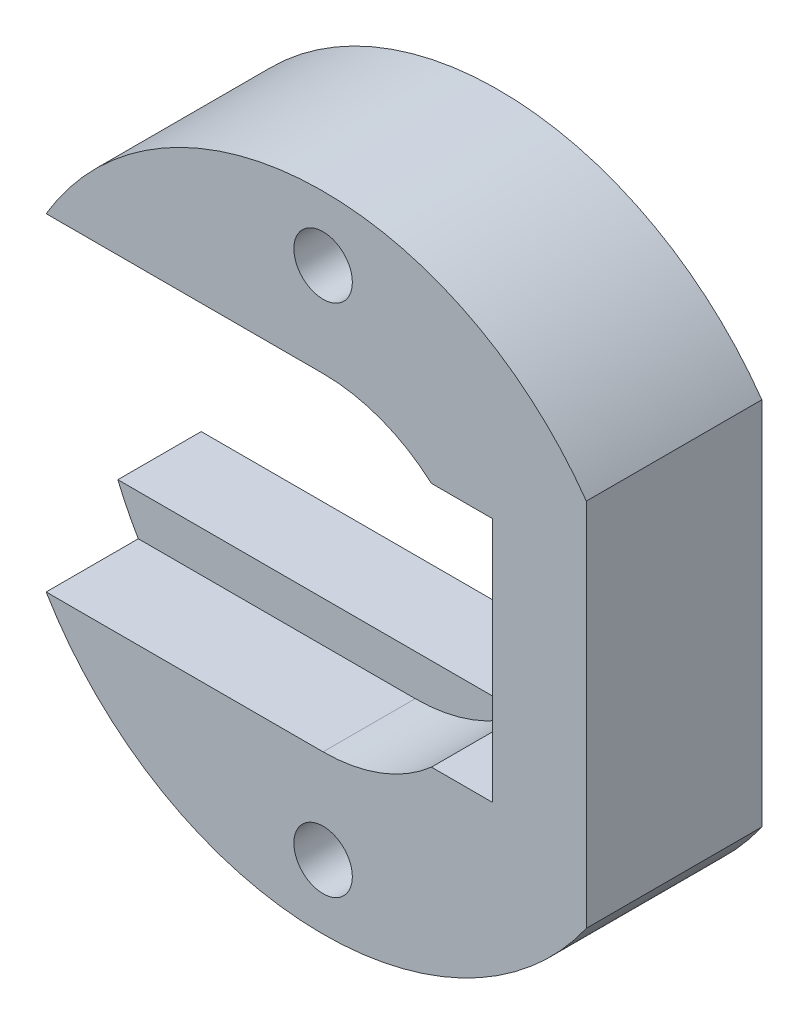
SolidWorks part; units mm, degrees
ref_plane "Front Plane" through (0, 0, 0) normal (0, 0, 1) x (1, 0, 0)
ref_plane "Top Plane" through (0, 0, 0) normal (0, 1, 0) x (1, 0, 0)
ref_plane "Right Plane" through (0, 0, 0) normal (1, 0, 0) x (0, 0, -1)
sketch "Sketch1" plane through (0, 0, 0) normal (0, 0, 1) x (1, 0, 0)
  circle A0 centre (0, 0) radius 34.925
  dimension "D1" = 69.85
extrude "Boss-Extrude1" add sketch "Sketch1" along normal blind 19.05
sketch "Sketch2" plane through (0, 0, 19.05) normal (0, 0, 1) x (1, 0, 0)
  line L1 (18.415, -13.335) -> (-88.265, -13.335)
  line L2 (18.415, -13.335) -> (18.415, 13.335)
  line L3 (18.415, 13.335) -> (-88.265, 13.335)
  line L4 (-88.265, -13.335) -> (-88.265, 13.335)
  line L5 (18.415, -13.335) -> (-88.265, 13.335) construction
  line L6 (18.415, 13.335) -> (-88.265, -13.335) construction
  circle A0 centre (0, 0) radius 34.925 construction
  point P0 (-34.925, 0)
  dimension "D1" = 26.67
  dimension "D2" = 106.68
extrude "Cut-Extrude1" cut sketch "Sketch2" against normal blind 19.05
sketch "Sketch4" plane through (0, 0, 19.05) normal (0, 0, 1) x (1, 0, 0)
  line L1 (0, -17.78) -> (-76.2, -17.78)
  line L2 (0, -17.78) -> (0, 17.78)
  line L3 (0, 17.78) -> (-76.2, 17.78)
  line L4 (-76.2, -17.78) -> (-76.2, 17.78)
  line L5 (0, -17.78) -> (-76.2, 17.78) construction
  line L6 (0, 17.78) -> (-76.2, -17.78) construction
  point P0 (-38.1, 0)
  dimension "D1" = 76.2
  dimension "D2" = 35.56
extrude "Cut-Extrude2" cut sketch "Sketch4" against normal blind 10
sketch "Sketch5" plane through (0, 0, 19.05) normal (0, 0, 1) x (1, 0, 0)
  circle A0 centre (0, 0) radius 17.78
  dimension "D1" = 35.56
extrude "Cut-Extrude3" cut sketch "Sketch5" against normal blind 10
sketch "Sketch6" plane through (0, 0, 19.05) normal (0, 0, 1) x (1, 0, 0)
  circle A0 centre (0, 27.94) radius 3.175
  circle A1 centre (0, -27.94) radius 3.175
  dimension "D1" = 6.35
  dimension "D2" = 6.35
extrude "Cut-Extrude4" cut sketch "Sketch6" against normal through all both and the other way through all
sketch "Sketch7" plane through (0, 0, 19.05) normal (0, 0, 1) x (1, 0, 0)
  line L1 (28.575, -53.2846) -> (41.275, -53.2846)
  line L2 (28.575, -53.2846) -> (28.575, 53.2846)
  line L3 (28.575, 53.2846) -> (41.275, 53.2846)
  line L4 (41.275, -53.2846) -> (41.275, 53.2846)
  line L5 (28.575, -53.2846) -> (41.275, 53.2846) construction
  line L6 (28.575, 53.2846) -> (41.275, -53.2846) construction
  arc A0 (-30.0604, -17.78) -> (-30.0604, 17.78) centre (0, 0) ccw construction
  point P0 (34.925, 0)
  dimension "D1" = 12.7
extrude "Cut-Extrude5" cut sketch "Sketch7" against normal through all both and the other way through all
